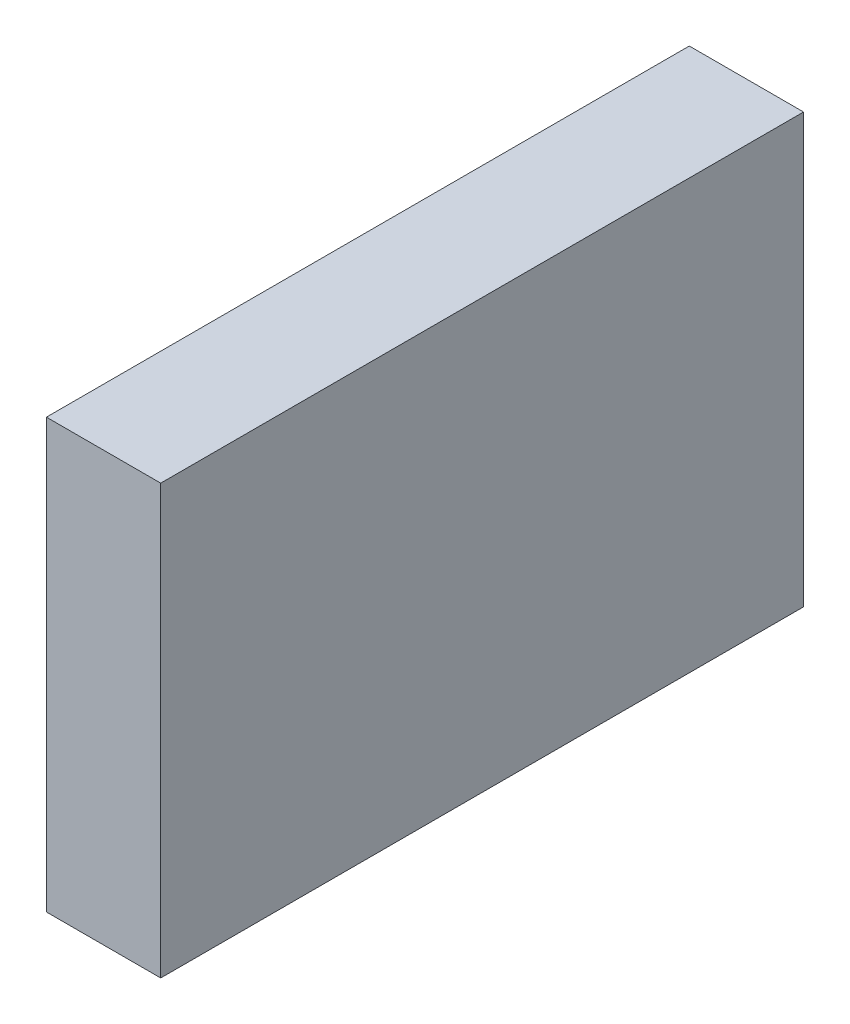
SolidWorks part; units mm, degrees
ref_plane "Front Plane" through (0, 0, 0) normal (0, 0, 1) x (1, 0, 0)
ref_plane "Top Plane" through (0, 0, 0) normal (0, 1, 0) x (1, 0, 0)
ref_plane "Right Plane" through (0, 0, 0) normal (1, 0, 0) x (0, 0, -1)
sketch "草圖1" plane through (0, 0, 0) normal (0, 0, 1) x (1, 0, 0)
  line L0 (-4, -15) -> (4, -15)
  line L1 (4, -15) -> (4, 15)
  line L2 (4, 15) -> (-4, 15)
  line L3 (-4, 15) -> (-4, -15)
extrude "填料-伸長1" add sketch "草圖1" along normal blind 45
